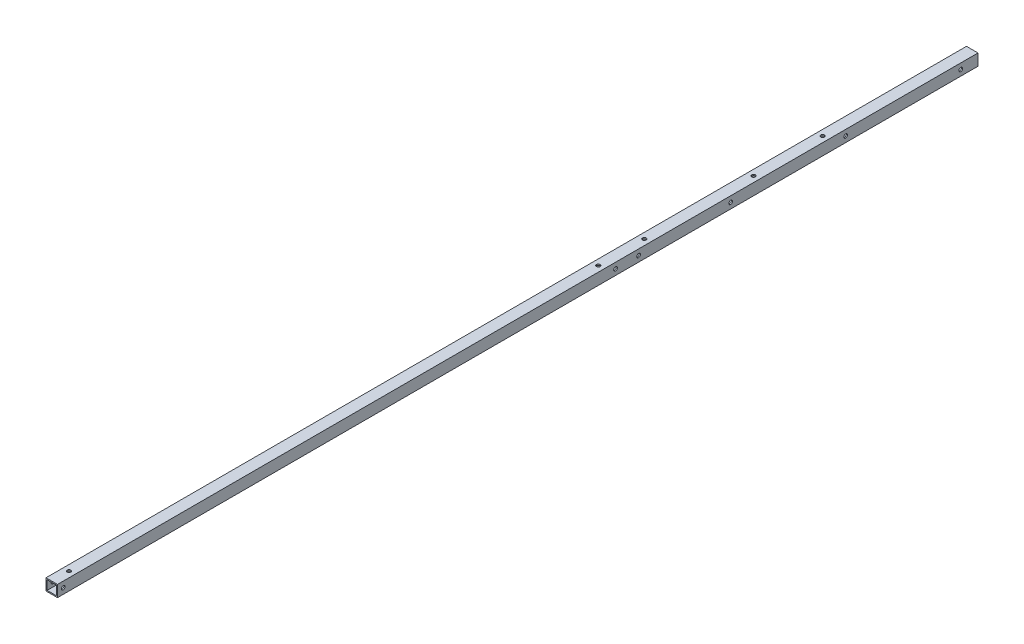
SolidWorks part; units mm, degrees
ref_plane "正面" through (0, 0, 0) normal (0, 0, 1) x (1, 0, 0)
ref_plane "平面" through (0, 0, 0) normal (0, 1, 0) x (1, 0, 0)
ref_plane "右側面" through (0, 0, 0) normal (1, 0, 0) x (0, 0, -1)
sketch "ｽｹｯﾁ1" plane through (0, 0, 0) normal (0, 0, 1) x (1, 0, 0)
  line L1 (-5, -5) -> (5, -5)
  line L2 (-5, -5) -> (-5, 5)
  line L3 (-5, 5) -> (5, 5)
  line L4 (5, -5) -> (5, 5)
  line L5 (-5, -5) -> (5, 5) construction
  line L6 (-5, 5) -> (5, -5) construction
  line L7 (-4, -4) -> (4, -4)
  line L8 (-4, -4) -> (-4, 4)
  line L9 (-4, 4) -> (4, 4)
  line L10 (4, -4) -> (4, 4)
  line L11 (-4, -4) -> (4, 4) construction
  line L12 (-4, 4) -> (4, -4) construction
  point P0 (0, 0)
  point P6 (0, 0)
  dimension "D1" = 1
  dimension "D2" = 10
  dimension "D3" = 10
extrude "ﾎﾞｽ - 押し出し1" add sketch "ｽｹｯﾁ1" along normal blind 800
sketch "ｽｹｯﾁ3" plane through (0, 5, 0) normal (0, 1, 0) x (1, 0, 0)
  line L0 (5, -800) -> (-5, -800) construction
  line L1 (-5, -800) -> (-5, 0) construction
  line L2 (5, -800) -> (5, 0) construction
  line L3 (-5, -800) -> (-5, 0) construction
  circle A0 centre (0, -785) radius 1.6
  circle A1 centre (0, -190) radius 1.6
  circle A2 centre (0, -130) radius 1.6
  circle A3 centre (0, -325) radius 1.6
  circle A4 centre (0, -285) radius 1.6
  point P18 (0, -800)
  dimension "D1" = 3.2
  dimension "D2" = 15
  dimension "D3" = 5
  dimension "D4" = 3.2
  dimension "D5" = 3.2
  dimension "D6" = 5
  dimension "D7" = 5
  dimension "D8" = 610
  dimension "D9" = 60
  dimension "D10" = 3.2
  dimension "D11" = 5
  dimension "D12" = 5
  dimension "D13" = 3.2
  dimension "D14" = 40
  dimension "D15" = 515
extrude "ｶｯﾄ - 押し出し2" cut sketch "ｽｹｯﾁ3" against normal through all
sketch "ｽｹｯﾁ4" plane through (-5, 0, 0) normal (-1, 0, 0) x (0, 0, 1)
  line L0 (800, 5) -> (800, -5) construction
  line L2 (800, 5) -> (0, 5) construction
  circle A0 centre (795, 0) radius 1.6
  circle A1 centre (295, 0) radius 1.6
  dimension "D1" = 3.2
  dimension "D2" = 5
  dimension "D3" = 5
  dimension "D4" = 3.2
  dimension "D5" = 500
  dimension "D6" = 5
extrude "ｶｯﾄ - 押し出し3" cut sketch "ｽｹｯﾁ4" against normal through all
sketch "ｽｹｯﾁ5" plane through (5, 0, 0) normal (1, 0, 0) x (0, 0, -1)
  line L0 (0, -5) -> (0, 5) construction
  line L1 (-800, 5) -> (0, 5) construction
  circle A0 centre (-15, 0) radius 1.6
  dimension "D1" = 15
  dimension "D2" = 3.2
  dimension "D3" = 5
extrude "ｶｯﾄ - 押し出し4" cut sketch "ｽｹｯﾁ5" against normal through all
pattern_linear "直線ﾊﾟﾀｰﾝ1" count 4 spacing 100 along (0, 0, 1) of "ｶｯﾄ - 押し出し4"
